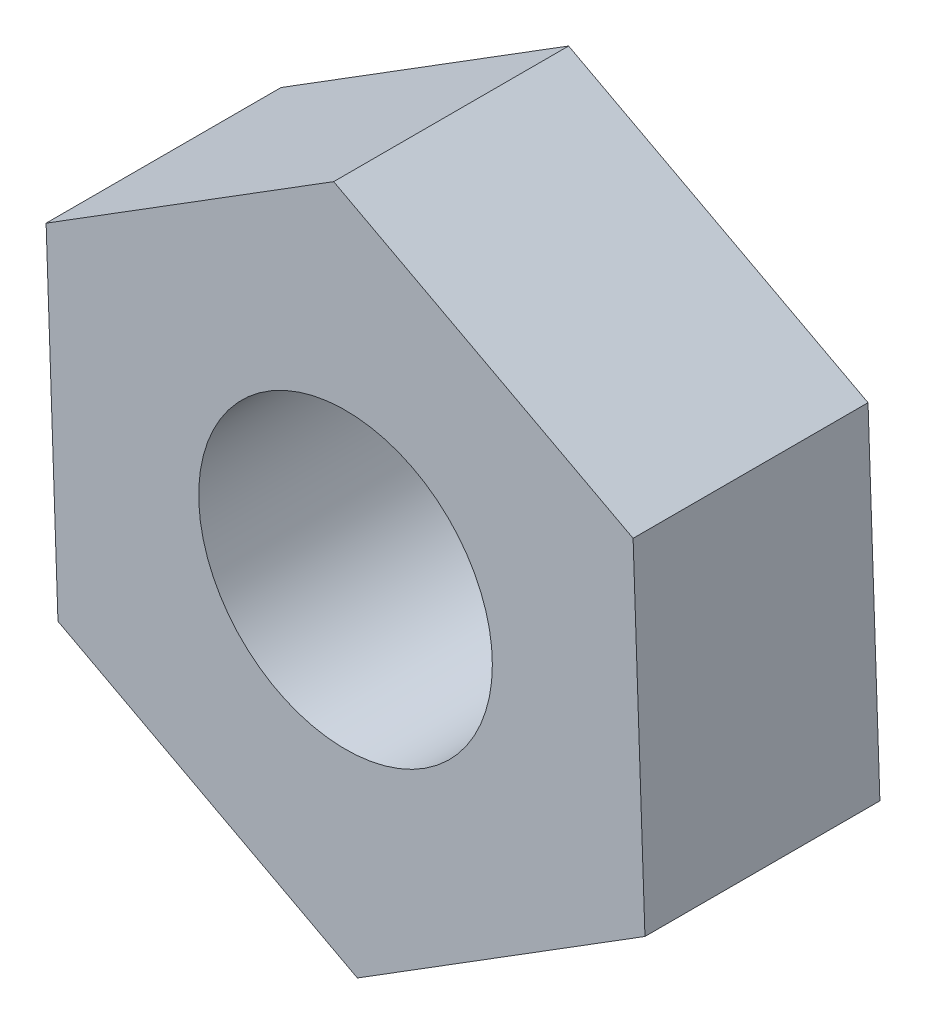
SolidWorks part; units mm, degrees
ref_plane "正面" through (0, 0, 0) normal (0, 0, 1) x (1, 0, 0)
ref_plane "平面" through (0, 0, 0) normal (0, 1, 0) x (1, 0, 0)
ref_plane "右側面" through (0, 0, 0) normal (1, 0, 0) x (0, 0, -1)
sketch "ｽｹｯﾁ1" plane through (0, 0, 0) normal (0, 0, 1) x (1, 0, 0)
  line L1 (1.9584, 1.224) -> (-0.0808, 2.308)
  line L2 (-0.0808, 2.308) -> (-2.0392, 1.084)
  line L3 (-2.0392, 1.084) -> (-1.9584, -1.224)
  line L4 (-1.9584, -1.224) -> (0.0808, -2.308)
  line L5 (0.0808, -2.308) -> (2.0392, -1.084)
  line L6 (2.0392, -1.084) -> (1.9584, 1.224)
  circle A0 centre (0, 0) radius 2 construction
  circle A1 centre (0, 0) radius 1
  dimension "D2" = 2
  dimension "D1" = 4
extrude "ﾎﾞｽ - 押し出し1" add sketch "ｽｹｯﾁ1" along normal blind 1.6
cosmetic thread "ねじ山1" parameters "D2"=12
